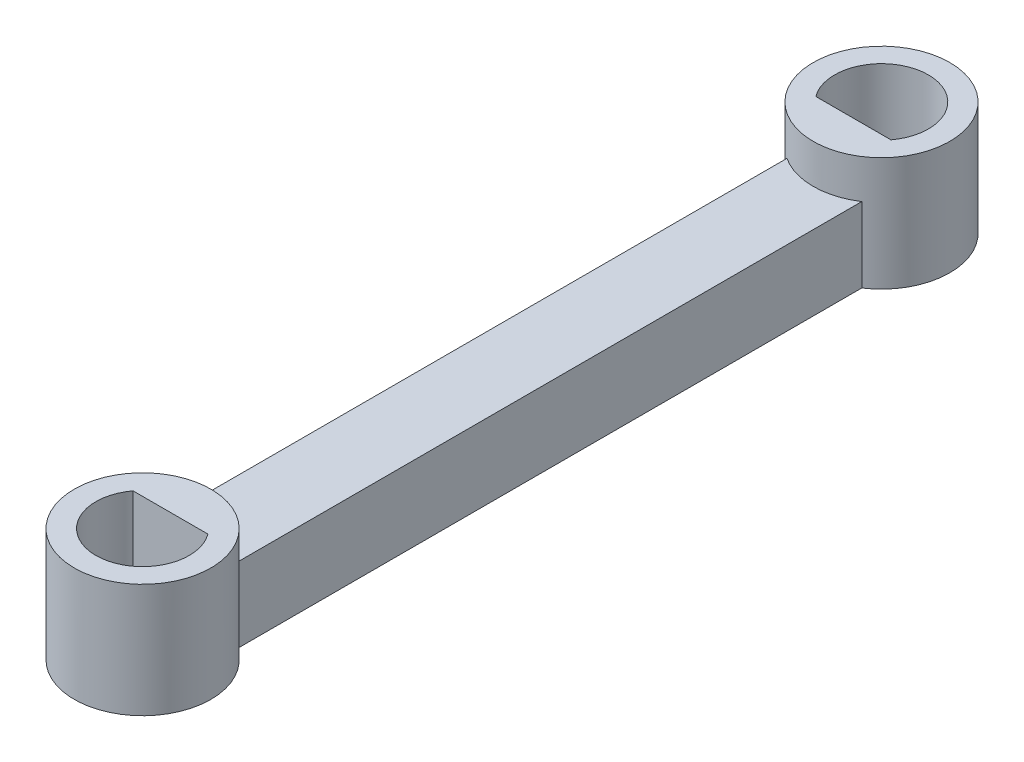
SolidWorks part; units mm, degrees
material "PET"
ref_plane "Front Plane" through (0, 0, 0) normal (0, 0, 1) x (1, 0, 0)
ref_plane "Top Plane" through (0, 0, 0) normal (0, 1, 0) x (1, 0, 0)
ref_plane "Right Plane" through (0, 0, 0) normal (1, 0, 0) x (0, 0, -1)
sketch "Sketch1" plane through (0, 0, 0) normal (0, 1, 0) x (1, 0, 0)
  line L0 (-3.2875, 2.45) -> (3.2875, 2.45)
  arc A0 (-3.2875, 2.45) -> (3.2875, 2.45) centre (0, 0) ccw
  circle A1 centre (0, 0) radius 6
  point P4 (0, 4.1)
  point P6 (0, 0)
  dimension "D1" = 8.2
  dimension "D2" = 12
  dimension "D3" = 1.65
extrude "Boss-Extrude1" add sketch "Sketch1" along normal blind 10
sketch "Sketch2" plane through (0, 0, -2.45) normal (0, 0, 1) x (1, 0, 0)
  line L0 (-3.2875, 10) -> (-3.2875, 0) construction
  line L1 (-3.2875, 6.575) -> (3.2875, 6.575)
  line L2 (-3.2875, 6.575) -> (-3.2875, 0)
  line L3 (-3.2875, 0) -> (3.2875, 0)
  line L4 (3.2875, 6.575) -> (3.2875, 0)
  line L5 (-3.2875, 6.575) -> (3.2875, 0) construction
  line L6 (-3.2875, 0) -> (3.2875, 6.575) construction
  line L7 (3.2875, 10) -> (3.2875, 0) construction
  line L8 (3.2875, 0) -> (-3.2875, 0) construction
  point P4 (0, 3.2875)
extrude "Boss-Extrude2" add sketch "Sketch2" against normal blind 60
ref_plane "Plane1" through (0, 0, -32.45) normal (0, 0, -1) x (-1, 0, 0)
mirror "Mirror1" about plane through (0, 0, -32.45) normal (0, 0, -1) of "Boss-Extrude1"
sketch "Sketch3" plane through (0, 10, 0) normal (0, 1, 0) x (1, 0, 0)
  line L2 (-3.2975, 62.43) -> (3.2975, 62.43)
  line L3 (-3.2975, 62.43) -> (3.2975, 62.43)
  arc A2 (3.2975, 62.43) -> (-3.2975, 62.43) centre (0, 64.9) ccw
  arc A3 (3.2975, 62.43) -> (-3.2975, 62.43) centre (0, 64.9) ccw
  dimension "D1" = 0.02
extrude "Cut-Extrude1" cut sketch "Sketch3" against normal through all
